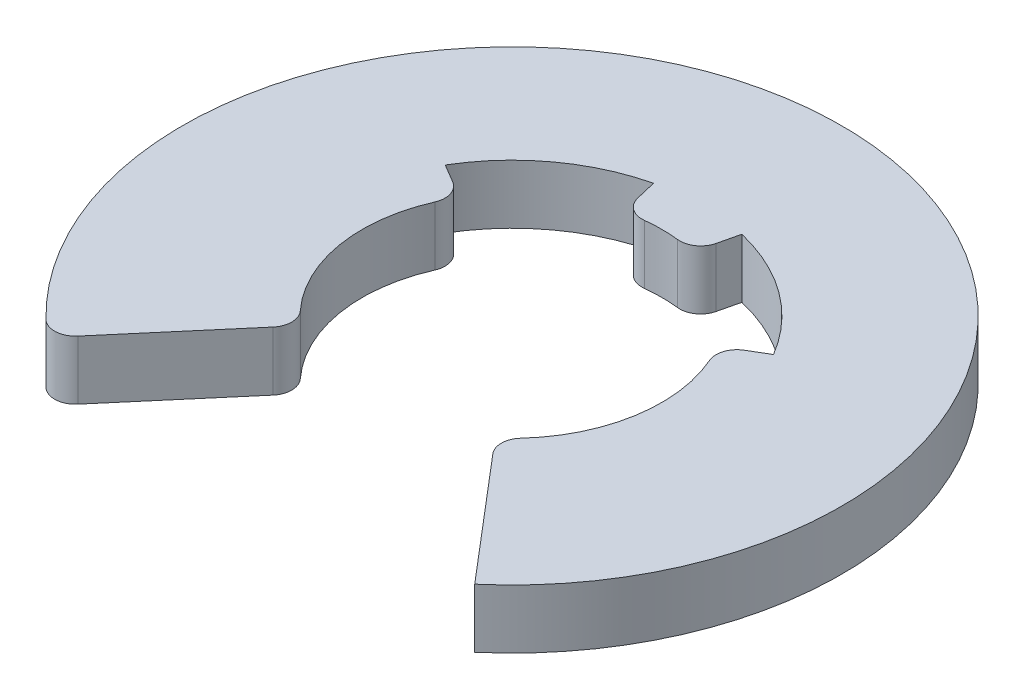
SolidWorks part; units mm, degrees
ref_plane "Front Plane" through (0, 0, 0) normal (0, 0, 1) x (1, 0, 0)
ref_plane "Top Plane" through (0, 0, 0) normal (0, 1, 0) x (1, 0, 0)
ref_plane "Right Plane" through (0, 0, 0) normal (1, 0, 0) x (0, 0, -1)
sketch "Sketch1" plane through (0, 0, 0) normal (0, 1, 0) x (1, 0, 0)
  line L0 (0, 0) -> (0, 1.08) construction
  line L1 (-0.3183, 1.3377) -> (-0.25, 1.0507)
  line L2 (-1.5394, -1.8086) -> (-0.7, -0.8224)
  line L3 (-1.1828, 0.7011) -> (-0.9291, 0.5507)
  line L4 (0.3183, 1.3377) -> (0.25, 1.0507)
  line L5 (1.1828, 0.7011) -> (0.9291, 0.5507)
  line L6 (1.5394, -1.8086) -> (0.7, -0.8224)
  arc A0 (1.5394, -1.8086) -> (-1.5394, -1.8086) centre (0, 0) ccw
  arc A1 (-0.9291, 0.5507) -> (-0.7, -0.8224) centre (0, 0) ccw
  arc A2 (1.1828, 0.7011) -> (0.3183, 1.3377) centre (0, 0) ccw
  circle A3 centre (0, 0) radius 2.375 construction
  circle A4 centre (0, 0) radius 1.375 construction
  arc A5 (-0.3183, 1.3377) -> (-1.1828, 0.7011) centre (0, 0) ccw
  arc A6 (0.25, 1.0507) -> (-0.25, 1.0507) centre (0, 0) ccw
  arc A7 (0.7, -0.8224) -> (0.9291, 0.5507) centre (0, 0) ccw
  dimension "D1" = 4.75
  dimension "D2" = 2.16
  dimension "D4" = 0.25
  dimension "D5" = 0.7
  dimension "D6" = 0.5
  dimension "D3" = 1
extrude "Boss-Extrude1" add sketch "Sketch1" along normal mid plane 0.425
fillet "Fillet1" radius 0.15 7 edges at (0.7, 0, 0.8224) (0.9291, 0, -0.5507) (0.25, 0, -1.0507) (-0.25, 0, -1.0507) (-0.9291, 0, -0.5507) (-0.7, 0, 0.8224) (-1.5394, 0, 1.8086)
